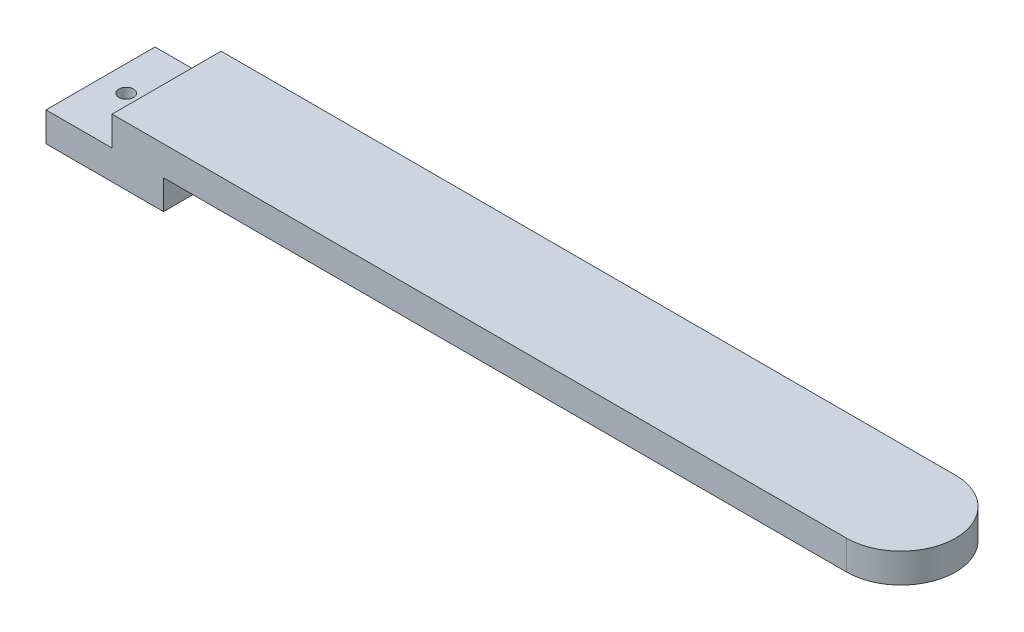
SolidWorks part; units mm, degrees
ref_plane "Front Plane" through (0, 0, 0) normal (0, 0, 1) x (1, 0, 0)
ref_plane "Top Plane" through (0, 0, 0) normal (0, 1, 0) x (1, 0, 0)
ref_plane "Right Plane" through (0, 0, 0) normal (1, 0, 0) x (0, 0, -1)
sketch "Sketch1" plane through (0, 0, 0) normal (0, 1, 0) x (1, 0, 0)
  line L0 (0, 14.84) -> (200, 14.84)
  line L1 (0, -14.84) -> (200, -14.84)
  line L2 (0, 14.84) -> (0, -14.84)
  arc A0 (200, 14.84) -> (200, -14.84) centre (200, 0) cw
  dimension "D1" = 14.84
  dimension "D2" = 14.84
  dimension "D3" = 200
extrude "Boss-Extrude1" add sketch "Sketch1" along normal blind 8
sketch "Sketch2" plane through (0, 0, 0) normal (0, 1, 0) x (1, 0, 0)
  line L0 (200, 14.84) -> (0, 14.84) construction
  line L1 (14, 14.84) -> (-18, 14.84)
  line L2 (14, 14.84) -> (14, -14.84)
  line L3 (14, -14.84) -> (-18, -14.84)
  line L4 (-18, 14.84) -> (-18, -14.84)
  line L5 (0, -14.84) -> (200, -14.84) construction
  line L6 (0, 14.84) -> (0, -14.84) construction
  circle A0 centre (-11, 0) radius 2
  dimension "D4" = 4
  dimension "D5" = 11
  dimension "D2" = 7
  dimension "D1" = 0
  dimension "D3" = 14
extrude "Boss-Extrude2" add sketch "Sketch2" against normal blind 8
